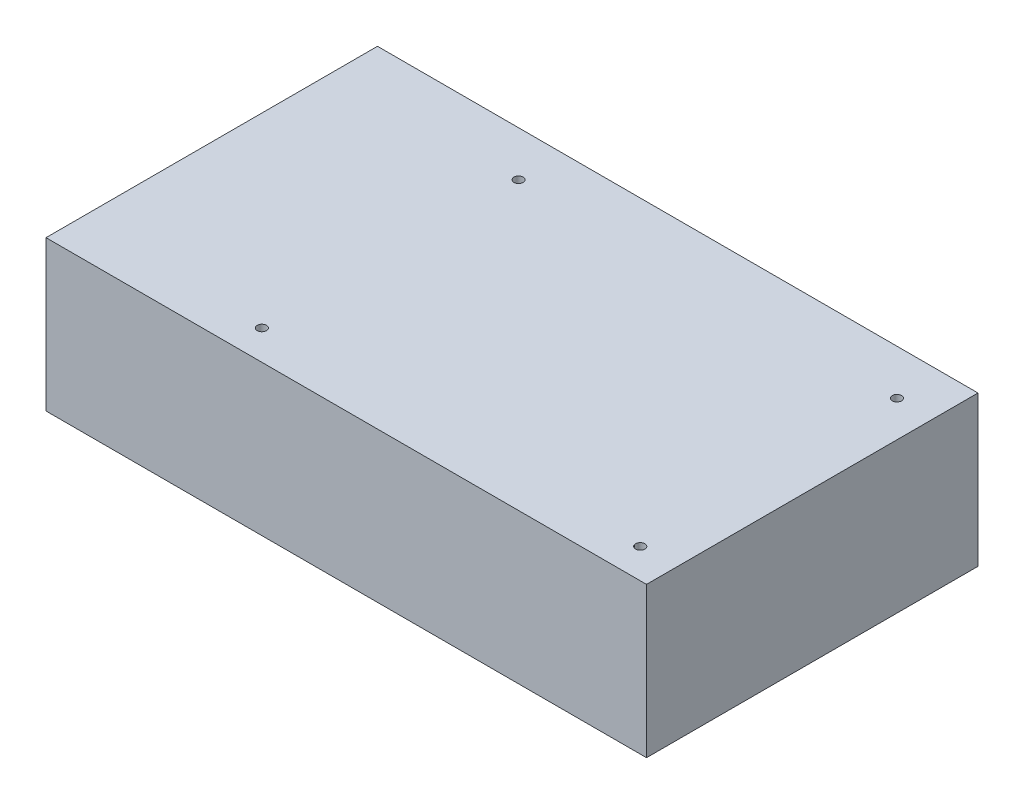
SolidWorks part; units mm, degrees
ref_plane "Front Plane" through (0, 0, 0) normal (0, 0, 1) x (1, 0, 0)
ref_plane "Top Plane" through (0, 0, 0) normal (0, 1, 0) x (1, 0, 0)
ref_plane "Right Plane" through (0, 0, 0) normal (1, 0, 0) x (0, 0, -1)
sketch "Sketch1" plane through (0, 0, 0) normal (0, 1, 0) x (1, 0, 0)
  line L1 (0, 0) -> (200, 0)
  line L2 (0, 0) -> (0, 110.4)
  line L3 (0, 110.4) -> (200, 110.4)
  line L4 (200, 0) -> (200, 110.4)
  dimension "D1" = 110.4
  dimension "D2" = 200
extrude "Boss-Extrude1" add sketch "Sketch1" along normal blind 50
sketch "Sketch2" plane through (0, 50, 0) normal (0, 1, 0) x (1, 0, 0)
  line L0 (62, 95.4) -> (188, 95.4) construction
  line L1 (62, 95.4) -> (62, 9.9) construction
  line L2 (188, 95.4) -> (188, 9.9) construction
  line L3 (62, 9.9) -> (188, 9.9) construction
  line L4 (200, 110.4) -> (0, 110.4) construction
  line L5 (200, 0) -> (200, 110.4) construction
  circle A0 centre (62, 95.4) radius 1.55
  circle A4 centre (188, 95.4) radius 1.55
  circle A5 centre (188, 9.9) radius 1.55
  circle A6 centre (62, 9.9) radius 1.55
  dimension "D5" = 3.1
  dimension "D1" = 15
  dimension "D2" = 12
  dimension "D3" = 126
  dimension "D4" = 85.5
  dimension "D6" = 2
  dimension "D7" = 2
extrude "Cut-Extrude1" cut sketch "Sketch2" against normal blind 10
